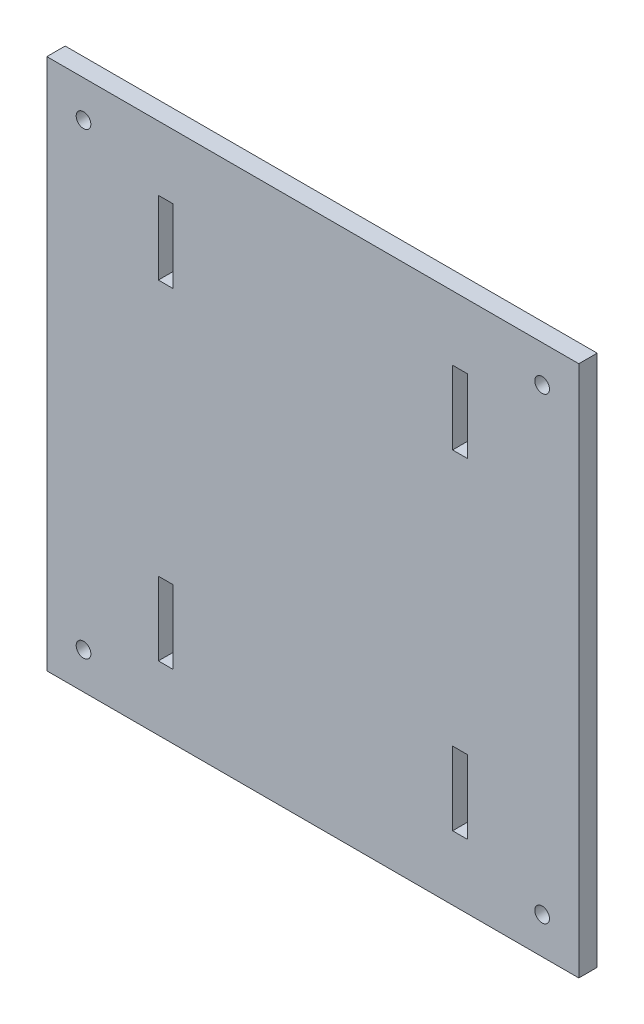
SolidWorks part; units mm, degrees
ref_plane "Plan de face" through (0, 0, 0) normal (0, 0, 1) x (1, 0, 0)
ref_plane "Plan de dessus" through (0, 0, 0) normal (0, 1, 0) x (1, 0, 0)
ref_plane "Plan de droite" through (0, 0, 0) normal (1, 0, 0) x (0, 0, -1)
sketch "Esquisse1" plane through (0, 0, 0) normal (0, 0, 1) x (1, 0, 0)
  line L1 (-32.9954, 86.4918) -> (112.0046, 86.4918)
  line L2 (-32.9954, 86.4918) -> (-32.9954, -58.5082)
  line L3 (-32.9954, -58.5082) -> (112.0046, -58.5082)
  line L4 (112.0046, 86.4918) -> (112.0046, -58.5082)
extrude "Boss.-Extru.1" add sketch "Esquisse1" along normal blind 5
sketch "Esquisse2" plane through (0, 0, 5) normal (0, 0, 1) x (1, 0, 0)
  line L0 (-32.9954, 86.4918) -> (-32.9954, -58.5082) construction
  line L2 (112.0046, 86.4918) -> (-32.9954, 86.4918) construction
  circle A0 centre (-22.9954, 76.4918) radius 2
  circle A1 centre (102.0046, 76.4918) radius 2
  circle A2 centre (102.0046, -48.5082) radius 2
  circle A3 centre (-22.9954, -48.5082) radius 2
  dimension "D1" = 125
  dimension "D2" = 125
  dimension "D3" = 10
  dimension "D4" = 10
sketch "Esquisse3" plane through (0, 0, 5) normal (0, 0, 1) x (1, 0, 0)
  line L0 (77.6046, 68.9418) -> (81.6046, 68.9418)
  line L1 (-2.5954, 68.9418) -> (1.4046, 68.9418)
  line L2 (-2.5954, 68.9418) -> (-2.5954, 48.9418)
  line L3 (-2.5954, 48.9418) -> (1.4046, 48.9418)
  line L4 (1.4046, 68.9418) -> (1.4046, 48.9418)
  line L5 (77.6046, 68.9418) -> (77.6046, 48.9418)
  line L6 (77.6046, 48.9418) -> (81.6046, 48.9418)
  line L7 (81.6046, 68.9418) -> (81.6046, 48.9418)
  line L8 (-2.5954, -20.9582) -> (1.4046, -20.9582)
  line L9 (-2.5954, -20.9582) -> (-2.5954, -40.9582)
  line L10 (-2.5954, -40.9582) -> (1.4046, -40.9582)
  line L11 (1.4046, -20.9582) -> (1.4046, -40.9582)
  line L12 (77.6046, -20.9582) -> (81.6046, -20.9582)
  line L13 (77.6046, -20.9582) -> (77.6046, -40.9582)
  line L14 (77.6046, -40.9582) -> (81.6046, -40.9582)
  line L15 (81.6046, -20.9582) -> (81.6046, -40.9582)
  line L16 (-2.5954, 68.9418) -> (-2.5954, 86.4918) construction
  line L18 (112.0046, 86.4918) -> (-32.9954, 86.4918) construction
  line L21 (-2.5954, -40.9582) -> (-2.5954, -58.5082) construction
  line L22 (-32.9954, -58.5082) -> (112.0046, -58.5082) construction
  line L23 (81.6046, 68.9418) -> (112.0046, 68.9418) construction
  line L25 (112.0046, -58.5082) -> (112.0046, 86.4918) construction
  line L26 (-32.9954, 68.9418) -> (-2.5954, 68.9418) construction
  line L27 (-32.9954, 86.4918) -> (-32.9954, -58.5082) construction
  dimension "D1" = 84.2
  dimension "D2" = 89.9
  dimension "D5" = 4
  dimension "D6" = 20
extrude "Enlèv. mat.-Extru.1" cut sketch "Esquisse3" against normal blind 5
extrude "Enlèv. mat.-Extru.2" cut sketch "Esquisse2" against normal blind 5
